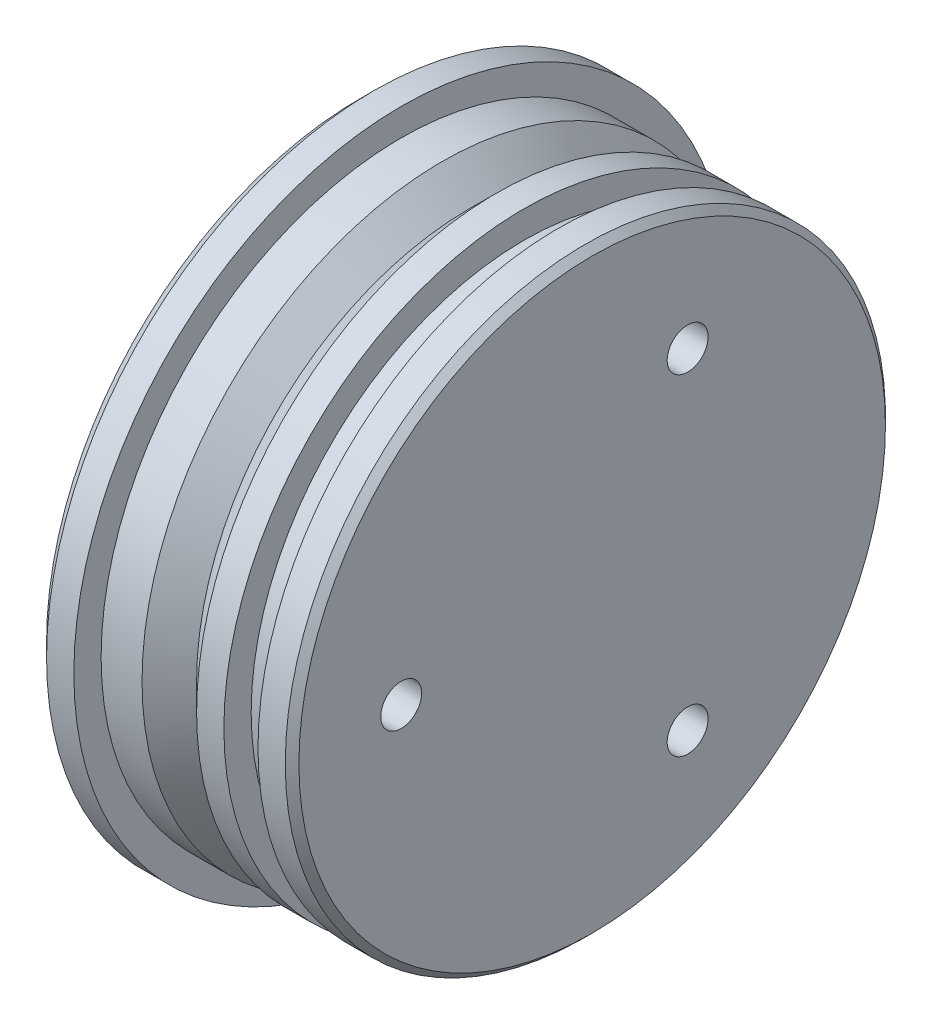
SolidWorks part; units mm, degrees
material "1060 Сплав"
ref_plane "Спереди" through (0, 0, 0) normal (0, 0, 1) x (1, 0, 0)
ref_plane "Сверху" through (0, 0, 0) normal (0, 1, 0) x (1, 0, 0)
ref_plane "Справа" through (0, 0, 0) normal (1, 0, 0) x (0, 0, -1)
sketch "Эскиз1" plane through (0, 0, 0) normal (0, 0, 1) x (1, 0, 0)
  line L0 (0, 0) -> (75.9362, 0) construction
  line L1 (-17, 0) -> (-17, 23)
  line L2 (-16, 24) -> (-14, 24)
  line L3 (-14, 24) -> (-14, 22)
  line L4 (-14, 22) -> (-11, 22)
  line L5 (-11, 22) -> (-9, 20)
  line L6 (-9, 20) -> (-7, 22)
  line L7 (-7, 22) -> (-5, 22)
  line L8 (-5, 22) -> (-5, 20)
  line L9 (-5, 20) -> (-2.5, 20)
  line L10 (-2.5, 20) -> (-2.5, 22)
  line L11 (-2.5, 22) -> (-0.5, 22)
  line L12 (0, 21.5) -> (0, 0)
  line L15 (-17, 23) -> (-16, 24)
  line L16 (-0.5, 22) -> (0, 21.5)
  line L18 (-17, 0) -> (0, 0)
  point P5 (-17, 24)
  point P16 (0, 22)
  dimension "D1" = 135
  dimension "D2" = 2
  dimension "D3" = 3
  dimension "D4" = 2.5
  dimension "D6" = 2
  dimension "D7" = 5
  dimension "D8" = 2
  dimension "D9" = 2.5
  dimension "D10" = 2
  dimension "D11" = 48
revolve "Повернуть1" add sketch "Эскиз1" angle 360 about L0
sketch "Эскиз2" plane through (0, 0, 0) normal (1, 0, 0) x (0, 0, -1)
  line L0 (0, 0) -> (-17.8433, 0) construction
  circle A0 centre (-14, 0) radius 1.5
  circle A1 centre (7, 12.1244) radius 1.5
  circle A2 centre (7, -12.1244) radius 1.5
  point P11 (0, 0)
  dimension "D1" = 3
  dimension "D2" = 14
  dimension "D3" = 3
extrude "Вырез-Вытянуть1" cut sketch "Эскиз2" against normal blind 10 contours A1 | A2 | A0
